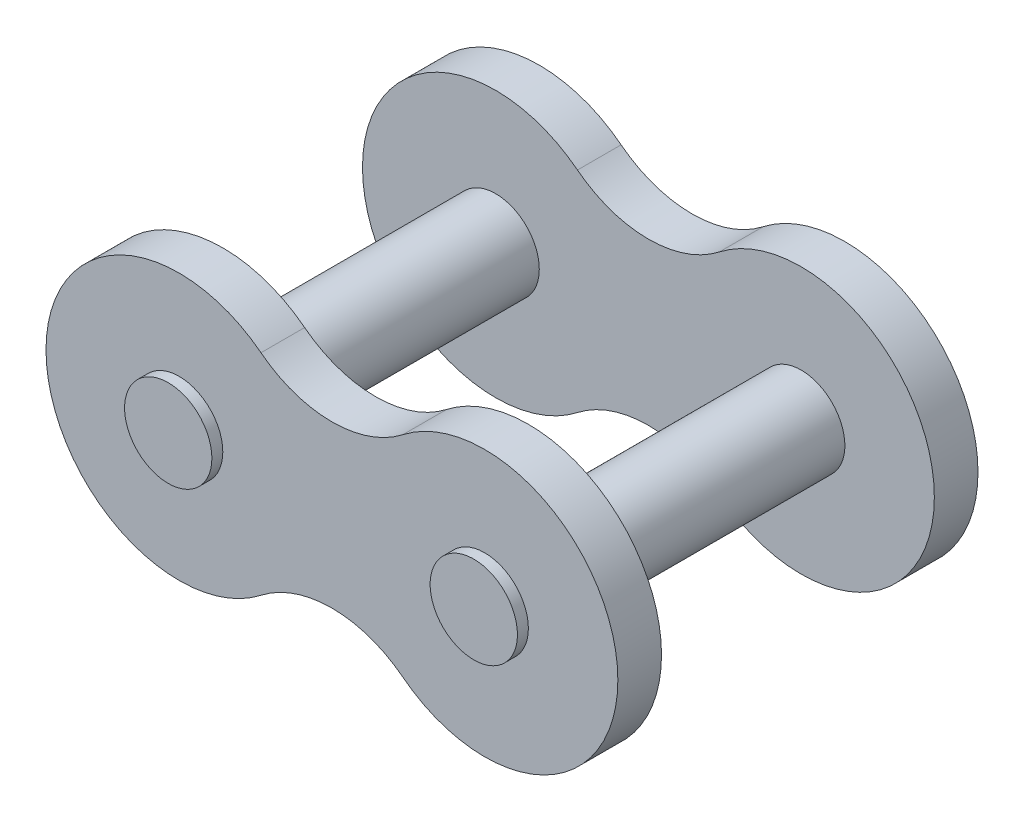
SolidWorks part; units mm, degrees
material "AISI 304"
ref_plane "Alzado" through (0, 0, 0) normal (0, 0, 1) x (1, 0, 0)
ref_plane "Planta" through (0, 0, 0) normal (0, 1, 0) x (1, 0, 0)
ref_plane "Vista lateral" through (0, 0, 0) normal (1, 0, 0) x (0, 0, -1)
sketch "Croquis1" plane through (0, 0, 0) normal (0, 0, 1) x (1, 0, 0)
  line L0 (0, 13.0829) -> (0, 3.6946) construction
  line L1 (-14.3186, 0) -> (16.5828, 0) construction
  line L2 (0, -3.6946) -> (0, -11.0763) construction
  arc A0 (-3.2504, 4.8115) -> (-3.2504, -4.8115) centre (-7, 0) ccw
  circle A1 centre (-7, 0) radius 2
  circle A2 centre (7, 0) radius 2
  arc A3 (3.2504, 4.8115) -> (3.2504, -4.8115) centre (7, 0) cw
  arc A4 (-3.2504, 4.8115) -> (3.2504, 4.8115) centre (0, 8.9826) ccw
  arc A5 (-3.2504, -4.8115) -> (3.2504, -4.8115) centre (0, -8.9826) cw
  dimension "D1" = 12.2
  dimension "D2" = 4
  dimension "D3" = 7
extrude "Saliente-Extruir1" add sketch "Croquis1" along normal blind 2
sketch "Croquis2" plane through (0, 0, 2) normal (0, 0, 1) x (1, 0, 0)
  circle A0 centre (7, 0) radius 2 construction
  circle A1 centre (7, 0) radius 2
  circle A2 centre (-7, 0) radius 2 construction
  circle A3 centre (-7, 0) radius 2
  arc A4 (-3.2504, 4.8115) -> (3.2504, 4.8115) centre (0, 8.9826) ccw
  arc A5 (-3.2504, 4.8115) -> (-3.2504, -4.8115) centre (-7, 0) ccw
  arc A6 (3.2504, -4.8115) -> (-3.2504, -4.8115) centre (0, -8.9826) ccw
  arc A7 (3.2504, -4.8115) -> (3.2504, 4.8115) centre (7, 0) ccw
  arc A8 (-3.2504, 4.8115) -> (3.2504, 4.8115) centre (0, 8.9826) ccw
  arc A9 (-3.2504, 4.8115) -> (-3.2504, -4.8115) centre (-7, 0) ccw
  arc A10 (3.2504, -4.8115) -> (-3.2504, -4.8115) centre (0, -8.9826) ccw
  arc A11 (3.2504, -4.8115) -> (3.2504, 4.8115) centre (7, 0) ccw
  dimension "D1" = 0
extrude "Saliente-Extruir2" add sketch "Croquis2" along normal blind 15 and the other way blind 2.5 contours A3 | A1
ref_plane "Plano1" through (0, 0, 8.25) normal (0, 0, 1) x (1, 0, 0)
mirror "Simetría1" about plane through (0, 0, 8.25) normal (0, 0, 1) of "Saliente-Extruir1"
